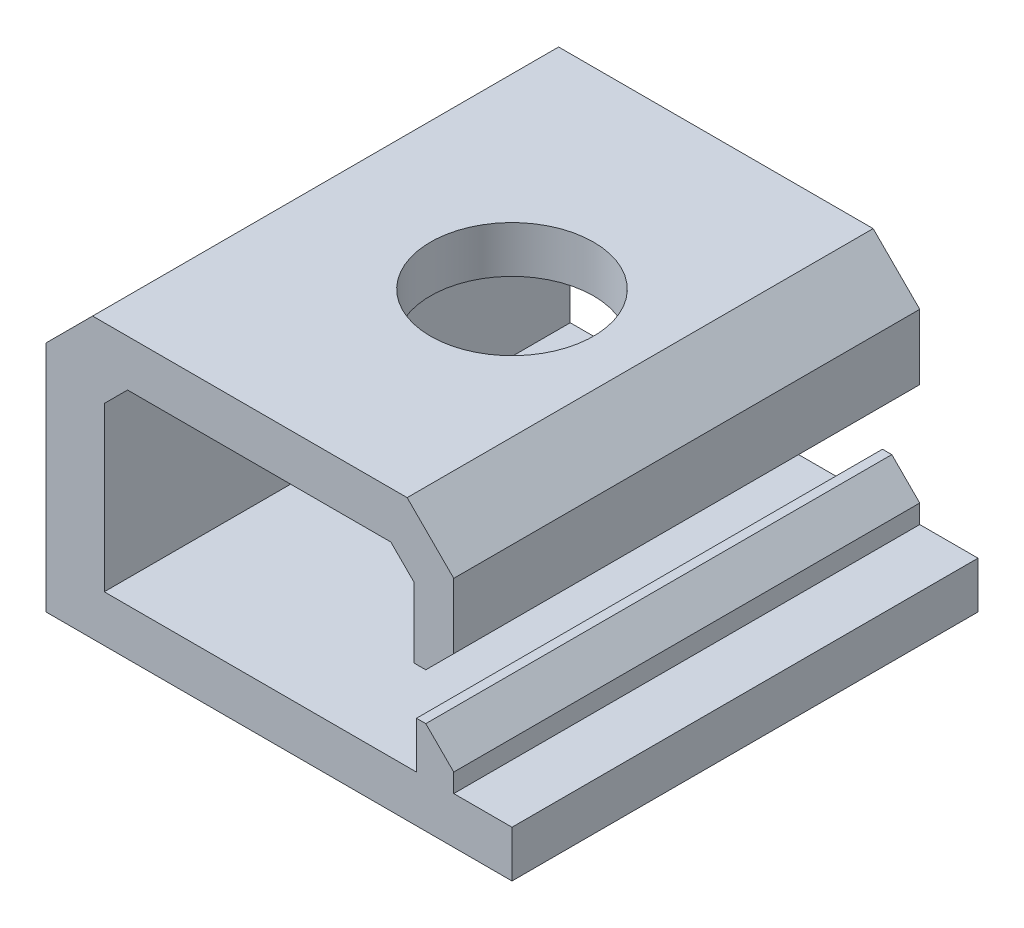
SolidWorks part; units mm, degrees
ref_plane "Front Plane" through (0, 0, 0) normal (0, 0, 1) x (1, 0, 0)
ref_plane "Top Plane" through (0, 0, 0) normal (0, 1, 0) x (1, 0, 0)
ref_plane "Right Plane" through (0, 0, 0) normal (1, 0, 0) x (0, 0, -1)
sketch "Sketch1" plane through (0, 0, 0) normal (0, 1, 0) x (1, 0, 0)
  line L1 (-10, -10) -> (10, -10)
  line L2 (-10, -10) -> (-10, 10)
  line L3 (-10, 10) -> (10, 10)
  line L4 (10, -10) -> (10, 10)
  line L5 (-10, -10) -> (10, 10) construction
  line L6 (-10, 10) -> (10, -10) construction
  circle A0 centre (0, 0) radius 1.75
  point P0 (0, 0)
  dimension "D3" = 3.5
  dimension "D1" = 20
  dimension "D2" = 20
extrude "Boss-Extrude1" add sketch "Sketch1" along normal blind 2
sketch "Sketch2" plane through (0, 2, 0) normal (0, 1, 0) x (1, 0, 0)
  line L0 (10, 10) -> (-10, 10) construction
  line L1 (-10, -10) -> (-7.5, -10)
  line L2 (-10, -10) -> (-10, 10)
  line L3 (-10, 10) -> (-7.5, 10)
  line L4 (-7.5, -10) -> (-7.5, 10)
  dimension "D1" = 2.5
extrude "Boss-Extrude2" add sketch "Sketch2" along normal blind 10
sketch "Sketch3" plane through (-7.5, 0, 0) normal (1, 0, 0) x (0, 0, -1)
  line L0 (-10, 12) -> (-10, 2) construction
  line L1 (10, 12) -> (-10, 12)
  line L2 (10, 12) -> (10, 10)
  line L3 (10, 10) -> (-10, 10)
  line L4 (-10, 12) -> (-10, 10)
  dimension "D1" = 2
extrude "Boss-Extrude3" add sketch "Sketch3" along normal blind 15
sketch "Sketch4" plane through (0, 10, 0) normal (0, -1, 0) x (1, 0, 0)
  line L0 (7.5, -10) -> (-7.5, -10) construction
  line L1 (7.5, 10) -> (5.8, 10)
  line L2 (7.5, 10) -> (7.5, -10)
  line L3 (7.5, -10) -> (5.8, -10)
  line L4 (5.8, 10) -> (5.8, -10)
  dimension "D1" = 1.7
extrude "Boss-Extrude4" add sketch "Sketch4" along normal blind 4
chamfer "Chamfer1" distance 1.2 angle 45 1 edges at (7.5, 6, 0)
chamfer "Chamfer2" distance 2 angle 45 2 edges at (-10, 12, 0) (7.5, 12, 0)
chamfer "Chamfer3" distance 1 angle 45 2 edges at (5.8, 10, 0) (-7.5, 10, 0)
sketch "Sketch5" plane through (0, 0, 0) normal (0, -1, 0) x (1, 0, 0)
  circle A0 centre (0, 0) radius 1.75
extrude "Cut-Extrude1" cut sketch "Sketch5" against normal blind 34
sketch "Sketch6" plane through (0, 12, 0) normal (0, 1, 0) x (1, 0, 0)
  circle A0 centre (0, 0) radius 3.5
  dimension "D1" = 7
extrude "Cut-Extrude2" cut sketch "Sketch6" against normal blind 2
sketch "Sketch7" plane through (0, 2, 0) normal (0, 1, 0) x (1, 0, 0)
  line L0 (-7.5, -10) -> (10, -10) construction
  line L1 (5.9, -10) -> (7.5, -10)
  line L2 (5.9, -10) -> (5.9, 10)
  line L3 (5.9, 10) -> (7.5, 10)
  line L4 (7.5, -10) -> (7.5, 10)
  line L5 (10, 10) -> (-7.5, 10) construction
  line L6 (10, -10) -> (10, 10) construction
  dimension "D1" = 2.5
  dimension "D2" = 1.6
extrude "Boss-Extrude5" add sketch "Sketch7" along normal blind 2
chamfer "Chamfer4" distance 1.2 angle 45 1 edges at (7.5, 4, 0)
